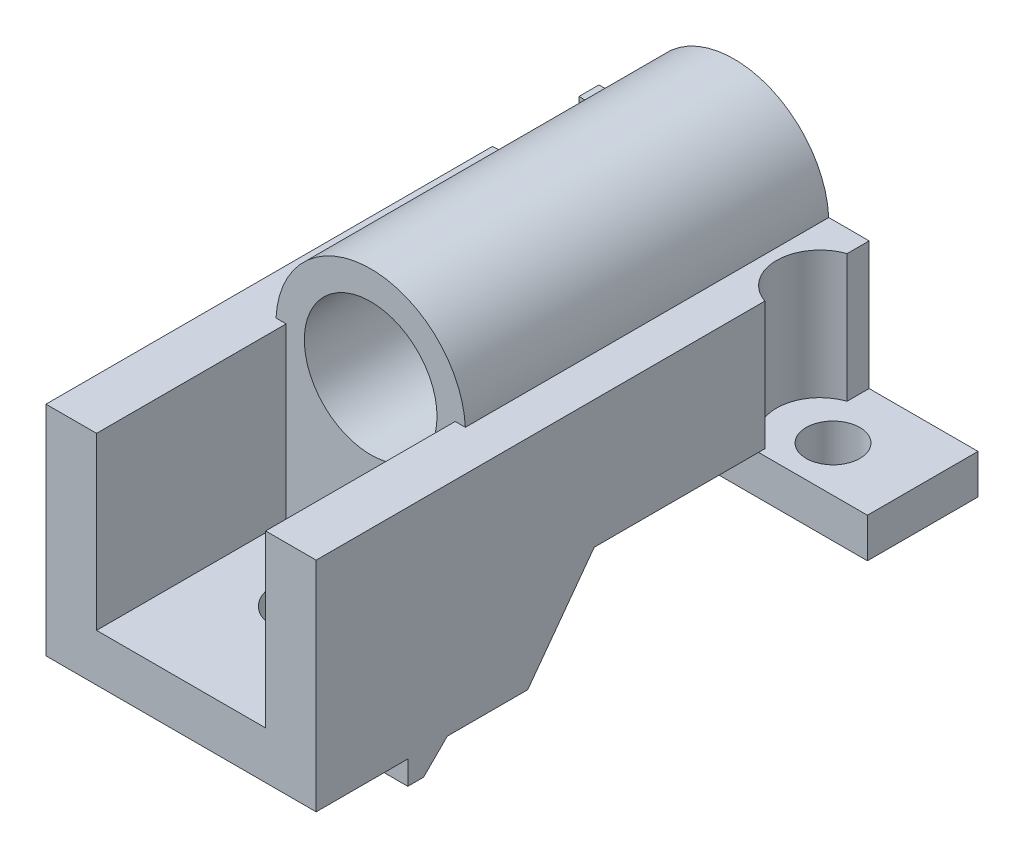
SolidWorks part; units mm, degrees
material "ABS"
ref_plane "Front Plane" through (0, 0, 0) normal (0, 0, 1) x (1, 0, 0)
ref_plane "Top Plane" through (0, 0, 0) normal (0, 1, 0) x (1, 0, 0)
ref_plane "Right Plane" through (0, 0, 0) normal (1, 0, 0) x (0, 0, -1)
sketch "Sketch1" plane through (0, 0, 0) normal (1, 0, 0) x (0, 0, -1)
  line L0 (0, 0) -> (0, -8.094)
  line L1 (0, -8.094) -> (-21.6094, -13.8)
  line L2 (-21.6094, -13.8) -> (-35, -13.8)
  line L3 (-35, -13.8) -> (-35, 0)
  line L4 (-35, 0) -> (0, 0)
  dimension "D1" = 35
  dimension "D2" = 8.094
  dimension "D3" = 13.8
  dimension "D4" = 13.3906
extrude "Boss-Extrude1" add sketch "Sketch1" along normal mid plane 17.1
sketch "Sketch2" plane through (0, 0, 35) normal (0, 0, 1) x (1, 0, 0)
  line L0 (8.55, 0) -> (-8.55, 0) construction
  line L1 (-5.35, 0) -> (5.35, 0)
  line L2 (-5.35, 0) -> (-5.35, -10.8)
  line L3 (-5.35, -10.8) -> (5.35, -10.8)
  line L4 (5.35, 0) -> (5.35, -10.8)
  line L5 (0, -10.8) -> (0, -13.8) construction
  line L6 (8.55, -13.8) -> (-8.55, -13.8) construction
  line L7 (-8.55, 0) -> (-8.55, -13.8) construction
  dimension "D1" = 3.2
  dimension "D2" = 10.8
extrude "Cut-Extrude1" cut sketch "Sketch2" against normal blind 12
sketch "Sketch3" plane through (0, 0, 23) normal (0, 0, 1) x (1, 0, 0)
  line L0 (5.35, 0) -> (-5.35, 0) construction
  circle A0 centre (0, -0.3017) radius 6
  dimension "D1" = 12
  dimension "D2" = 0.3018
extrude "Boss-Extrude2" add sketch "Sketch3" against normal through all
sketch "Sketch4" plane through (0, 0, 23) normal (0, 0, 1) x (1, 0, 0)
  circle A0 centre (0, -0.3017) radius 4.2
  dimension "D1" = 8.4
extrude "Cut-Extrude2" cut sketch "Sketch4" against normal through all
sketch "Sketch8" plane through (8.55, 0, 0) normal (1, 0, 0) x (0, 0, -1)
  line L0 (-29.2, -13.8) -> (-29.2, -15.3)
  line L1 (-35, -13.8) -> (-21.6094, -13.8) construction
  line L2 (-29.2, -15.3) -> (-28.2, -15.3)
  line L3 (-28.2, -15.3) -> (-26.7, -13.8)
  line L4 (-26.7, -13.8) -> (-29.2, -13.8)
  line L12 (-35, 0) -> (-35, -13.8) construction
  dimension "D1" = 1
  dimension "D2" = 1.5
  dimension "D3" = 2.5
  dimension "D4" = 5.8
extrude "Boss-Extrude5" add sketch "Sketch8" against normal through all
sketch "Sketch10" plane through (0, 0, 29.2) normal (0, 0, 1) x (1, 0, 0)
  line L0 (8.55, -13.8) -> (8.55, -15.3) construction
  line L1 (-4.05, -13.8) -> (4.05, -13.8)
  line L2 (-4.05, -13.8) -> (-4.05, -15.3)
  line L3 (-4.05, -15.3) -> (4.05, -15.3)
  line L4 (4.05, -13.8) -> (4.05, -15.3)
  line L5 (-8.55, -15.3) -> (8.55, -15.3) construction
  line L6 (-8.55, -13.8) -> (8.55, -13.8) construction
  line L7 (0, -13.8) -> (0, -10.8) construction
  line L8 (8.55, -13.8) -> (-8.55, -13.8) construction
  line L9 (-5.35, -10.8) -> (5.35, -10.8) construction
  dimension "D1" = 4.5
extrude "Cut-Extrude4" cut sketch "Sketch10" against normal up to next
sketch "Sketch7" plane through (0, -10.8, 0) normal (0, 1, 0) x (1, 0, 0)
  line L0 (0, -27) -> (0, -35) construction
  line L1 (-5.35, -35) -> (5.35, -35) construction
  circle A0 centre (0, -27) radius 2.2
  dimension "D1" = 4.4
  dimension "D2" = 8
extrude "Cut-Extrude3" cut sketch "Sketch7" against normal through all
sketch "Sketch18" plane through (0, 0, 0) normal (0, 0, -1) x (-1, 0, 0)
  line L0 (-5.35, -3.0179) -> (-5.35, -13.8)
  line L1 (-4.05, -13.8) -> (-8.55, -13.8) construction
  line L2 (-5.35, -13.8) -> (5.35, -13.8)
  line L3 (8.55, -13.8) -> (4.05, -13.8) construction
  line L4 (5.35, -13.8) -> (5.35, -3.0179)
  arc A0 (-5.35, -3.0179) -> (5.35, -3.0179) centre (0, -0.3017) ccw
  dimension "D1" = 12
  dimension "D2" = 10.7
extrude "Cut-Extrude9" cut sketch "Sketch18" against normal blind 22
sketch "Sketch14" plane through (0, 0, 0) normal (1, 0, 0) x (0, 0, -1)
  line L0 (-20, -13.8) -> (-17.002, -10.594)
  line L1 (0, -4.8) -> (-22, -4.8)
  line L3 (-20, -13.8) -> (-22, -13.8)
  line L4 (-22, -13.8) -> (-22, -4.8)
  line L7 (-26.7, -13.8) -> (-21.6094, -13.8) construction
  line L10 (-17.002, -10.594) -> (0, -10.594)
  line L11 (0, -4.8) -> (0, -10.594)
  dimension "D1" = 2
  dimension "D2" = 133.08
  dimension "D3" = 9
  dimension "D4" = 3.206
extrude "Boss-Extrude6" add sketch "Sketch14" along normal mid plane 3.106
sketch "Sketch16" plane through (0, 0, 0) normal (0, 0, -1) x (-1, 0, 0)
  line L0 (-8.55, -8.094) -> (-8.55, 0) construction
  line L1 (-15.44, -10.594) -> (12.56, -10.594)
  line L2 (-15.44, -10.594) -> (-15.44, -8.094)
  line L4 (-15.44, -8.094) -> (12.56, -8.094)
  line L5 (12.56, -10.594) -> (12.56, -8.094)
  line L6 (-8.55, 0) -> (-5.9924, 0) construction
  dimension "D1" = 28
  dimension "D2" = 2.5
  dimension "D3" = 8.094
  dimension "D4" = 6.89
extrude "Boss-Extrude8" add sketch "Sketch16" against normal blind 7
sketch "Sketch17" plane through (8.55, 0, 0) normal (1, 0, 0) x (0, 0, -1)
  line L0 (-7, -8.094) -> (-17.4, -8.094)
  line L1 (-17.4, -8.094) -> (-21.6094, -13.8)
  line L2 (-26.7, -13.8) -> (-21.6094, -13.8) construction
  line L3 (-35, 0) -> (-35, -13.8) construction
  line L4 (-21.6094, -13.8) -> (-7, -13.8)
  line L5 (-7, -13.8) -> (-7, -8.094)
  dimension "D1" = 10.4
  dimension "D2" = 13.3906
extrude "Cut-Extrude8" cut sketch "Sketch17" against normal up to surface (6.997 mm away) up to face at (1.553, -9.6463, 11.8752)
sketch "Sketch19" plane through (1.553, 0, 0) normal (1, 0, 0) x (0, 0, -1)
  line L0 (-17.002, -10.594) -> (-7, -10.594) construction
  circle A0 centre (-9.5002, -11.9282) radius 2.8339
  dimension "D1" = 5.6679
  dimension "D2" = 1.3342
extrude "Cut-Extrude10" cut sketch "Sketch19" against normal up to next
sketch "Sketch20" plane through (0, -8.094, 0) normal (0, 1, 0) x (1, 0, 0)
  line L0 (-9.0628, -4.126) -> (10.3901, -4.126) construction
  line L3 (8.55, 0) -> (15.44, 0) construction
  line L4 (15.44, -7) -> (15.44, 0) construction
  circle A0 centre (-9.0628, -4.126) radius 1.7
  circle A1 centre (10.3901, -4.126) radius 1.7
  dimension "D1" = 3.4
  dimension "D2" = 4.126
  dimension "D3" = 5.0499
  dimension "D4" = 19.4529
extrude "Cut-Extrude11" cut sketch "Sketch20" against normal through all both and the other way through all
sketch "Sketch21" plane through (0, -8.094, 0) normal (0, 1, 0) x (1, 0, 0)
  line L0 (-12.56, -7) -> (-8.55, -7) construction
  line L1 (15.44, -7) -> (15.44, 0) construction
  circle A0 centre (-8.56, -4) radius 2.75
  circle A1 centre (9.44, -4) radius 2.75
  dimension "D1" = 5.5
  dimension "D2" = 3
  dimension "D3" = 18
  dimension "D4" = 6
extrude "Cut-Extrude12" cut sketch "Sketch21" along normal through all
sketch "Sketch22" plane through (-8.55, 0, 0) normal (-1, 0, 0) x (0, 0, 1)
  line L0 (17.4, -8.094) -> (7, -8.094)
  line L1 (17.4, -8.094) -> (21.6094, -13.8)
  line L2 (7, -9.9424) -> (7, -8.094)
  line L3 (7, -9.9424) -> (21.6094, -13.8)
extrude "Cut-Extrude13" cut sketch "Sketch22" against normal up to next
